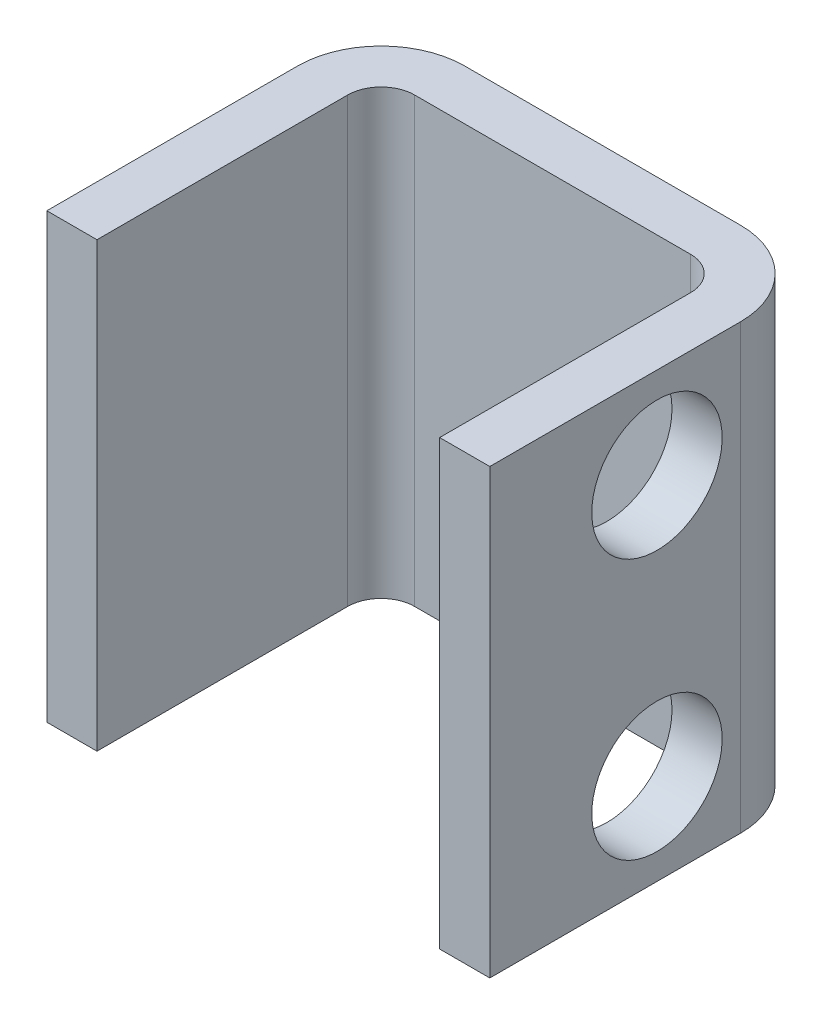
SolidWorks part; units mm, degrees
ref_plane "Front Plane" through (0, 0, 0) normal (1, 0, 0) x (0, 1, 0)
ref_plane "Top Plane" through (0, 0, 0) normal (0, 0, 1) x (0, 1, 0)
ref_plane "Right Plane" through (0, 0, 0) normal (0, 1, 0) x (-1, 0, 0)
sketch "Sketch4" plane through (0, 0, 0) normal (0, 0, 1) x (0, 1, 0)
  line L1 (13.25, -13.25) -> (-13.25, -13.25)
  line L2 (13.25, -13.25) -> (13.25, 13.25)
  line L3 (13.25, 13.25) -> (-13.25, 13.25)
  line L4 (-13.25, -13.25) -> (-13.25, 13.25)
  line L5 (13.25, -13.25) -> (-13.25, 13.25) construction
  line L6 (13.25, 13.25) -> (-13.25, -13.25) construction
  point P0 (0, 0)
  dimension "D1" = 26.5
extrude "Boss-Extrude2" add sketch "Sketch4" along normal blind 20
shell "Shell1" thickness 3
sketch "Sketch6" plane through (13.25, 0, 0) normal (1, 0, 0) x (0, 1, 0)
  line L0 (0, 20) -> (0, 0) construction
  line L1 (-13.25, 20) -> (13.25, 20) construction
  line L2 (-13.25, 10) -> (13.25, 10) construction
  line L3 (-13.25, 20) -> (-13.25, 0) construction
  line L4 (13.25, 20) -> (13.25, 0) construction
  line L5 (0, 10) -> (-13.25, 10) construction
  line L6 (-13.25, 10) -> (0, 10) construction
  line L7 (0, 10) -> (-3.9, 10)
  circle A0 centre (-7.8, 10) radius 3.9
  circle A1 centre (7.8, 10) radius 3.9
  point P16 (-6.625, 10)
  dimension "D1" = 7.8
  dimension "D2" = 3.9
extrude "Cut-Extrude2" cut sketch "Sketch6" against normal up to surface (23.5 mm away) contours A0 | A1 up to face at (-10.25, 0, 11.5)
fillet "Fillet3" radius 5 2 edges at (13.25, 0, 0) (-13.25, 0, 0)
fillet "Fillet4" radius 2 2 edges at (-10.25, 0, 3) (10.25, 0, 3)
